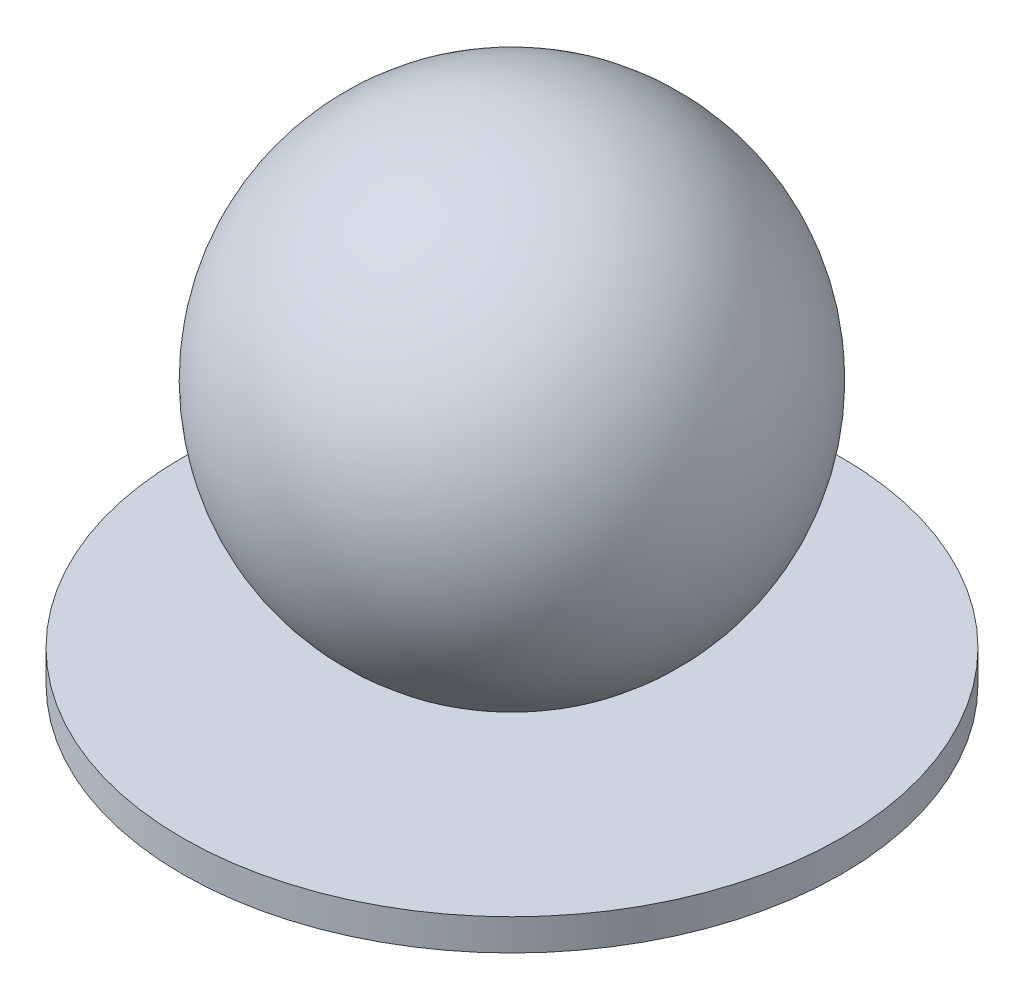
SolidWorks part; units mm, degrees
ref_plane "前视基准面" through (0, 0, 0) normal (0, 0, 1) x (1, 0, 0)
ref_plane "上视基准面" through (0, 0, 0) normal (0, 1, 0) x (1, 0, 0)
ref_plane "右视基准面" through (0, 0, 0) normal (1, 0, 0) x (0, 0, -1)
sketch "草图1" plane through (0, 0, 0) normal (0, 0, 1) x (1, 0, 0)
  line L1 (0, 0) -> (0, 7.5)
  line L2 (0, 0) -> (0, -7.5)
  arc A0 (0, 7.5) -> (0, -7.5) centre (0, 0) ccw
  dimension "D1" = 15
revolve "旋转4" add sketch "草图1" angle 360 about L1
ref_plane "基准面4" through (0, -7.4, 0) normal (0, 1, 0) x (1, 0, 0)
sketch "草图3" plane through (0, -7.4, 0) normal (0, 1, 0) x (1, 0, 0)
  circle A0 centre (0, 0) radius 10.5
  dimension "D1" = 21
extrude "凸台-拉伸1" add sketch "草图3" against normal blind 1 separate body
sketch "草图4" plane through (0, -8.4, 0) normal (0, -1, 0) x (1, 0, 0)
  circle A0 centre (0, 0) radius 0.75
  dimension "D1" = 1.5
extrude "切除-拉伸1" cut sketch "草图4" against normal blind 0.5
